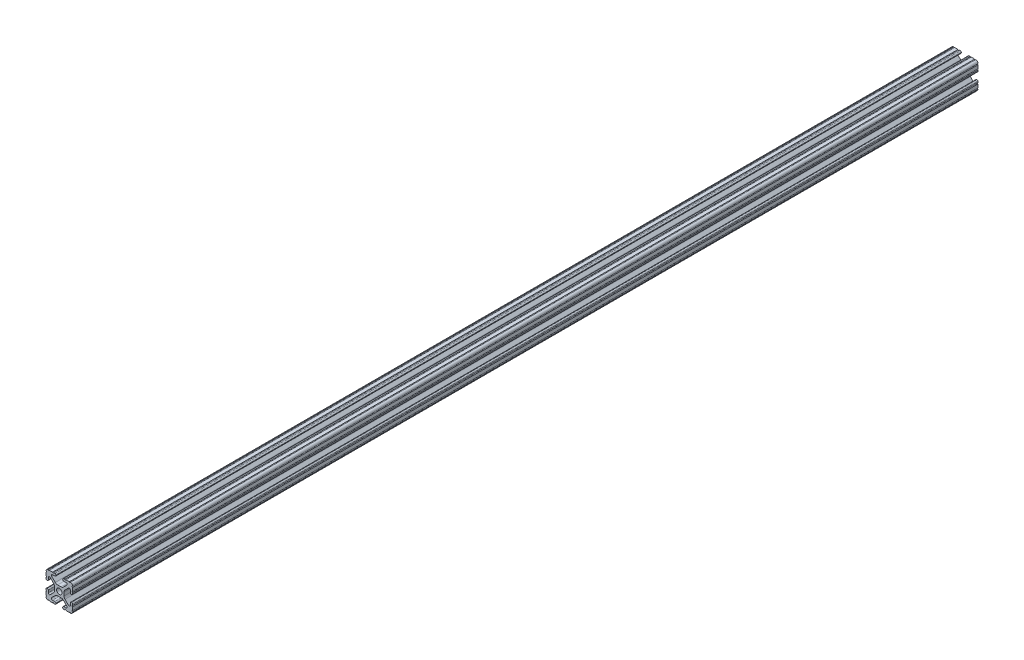
SolidWorks part; units mm, degrees
ref_plane "Front Plane" through (0, 0, 0) normal (0, 0, 1) x (1, 0, 0)
ref_plane "Top Plane" through (0, 0, 0) normal (0, 1, 0) x (1, 0, 0)
ref_plane "Right Plane" through (0, 0, 0) normal (1, 0, 0) x (0, 0, -1)
sketch "Sketch1" plane through (0, 0, 0) normal (0, 0, 1) x (1, 0, 0)
  line L88 (-7.1797, -8.6452) -> (-3.9523, -5.4237)
  line L89 (-1.7093, -4.4958) -> (1.7093, -4.4958)
  line L90 (3.9523, -5.4237) -> (7.1797, -8.6452)
  line L91 (6.4164, -10.4902) -> (4.2875, -10.4902)
  line L92 (3.2385, -11.5392) -> (3.2385, -11.651)
  line L93 (4.2875, -12.7) -> (5.3171, -12.7)
  line L94 (6.3331, -12.7) -> (9.5504, -12.7)
  line L95 (12.7, -9.5504) -> (12.7, -6.3331)
  line L96 (12.7, -5.3171) -> (12.7, -4.2875)
  line L97 (11.651, -3.2385) -> (11.5392, -3.2385)
  line L98 (10.4902, -4.2875) -> (10.4902, -6.4021)
  line L99 (8.7371, -7.1294) -> (5.441, -3.8408)
  line L100 (4.5085, -1.5932) -> (4.5085, 1.5932)
  line L101 (5.441, 3.8408) -> (8.7371, 7.1294)
  line L102 (10.4902, 6.4021) -> (10.4902, 4.2875)
  line L103 (11.5392, 3.2385) -> (11.651, 3.2385)
  line L104 (12.7, 4.2875) -> (12.7, 5.3171)
  line L105 (12.7, 6.3331) -> (12.7, 9.5504)
  line L106 (9.5504, 12.7) -> (6.3331, 12.7)
  line L107 (5.3171, 12.7) -> (4.2875, 12.7)
  line L108 (3.2385, 11.651) -> (3.2385, 11.5392)
  line L109 (4.2875, 10.4902) -> (6.4768, 10.4902)
  line L110 (7.207, 8.7244) -> (3.8983, 5.4232)
  line L111 (1.6558, 4.4958) -> (-1.6558, 4.4958)
  line L112 (-3.8983, 5.4232) -> (-7.207, 8.7244)
  line L113 (-6.4768, 10.4902) -> (-4.2875, 10.4902)
  line L114 (-3.2385, 11.5392) -> (-3.2385, 11.651)
  line L115 (-4.2875, 12.7) -> (-5.3171, 12.7)
  line L116 (-6.3331, 12.7) -> (-9.5504, 12.7)
  line L117 (-12.7, 9.5504) -> (-12.7, 6.3331)
  line L118 (-12.7, 5.3171) -> (-12.7, 4.2875)
  line L119 (-11.651, 3.2385) -> (-11.5392, 3.2385)
  line L120 (-10.4902, 4.2875) -> (-10.4902, 6.4021)
  line L121 (-8.7371, 7.1294) -> (-5.441, 3.8408)
  line L122 (-4.5085, 1.5932) -> (-4.5085, -1.5932)
  line L123 (-5.441, -3.8408) -> (-8.7371, -7.1294)
  line L124 (-10.4902, -6.4021) -> (-10.4902, -4.2875)
  line L125 (-11.5392, -3.2385) -> (-11.651, -3.2385)
  line L126 (-12.7, -4.2875) -> (-12.7, -5.3171)
  line L127 (-12.7, -6.3331) -> (-12.7, -9.5504)
  line L128 (-9.5504, -12.7) -> (-6.3331, -12.7)
  line L129 (-5.3171, -12.7) -> (-4.2875, -12.7)
  line L130 (-3.2385, -11.651) -> (-3.2385, -11.5392)
  line L131 (-4.2875, -10.4902) -> (-6.4164, -10.4902)
  circle A1 centre (0, 0) radius 2.6035
  arc A104 (-7.1797, -8.6452) -> (-6.4164, -10.4902) centre (-6.4164, -9.4098) ccw
  arc A105 (-1.7093, -4.4958) -> (-3.9523, -5.4237) centre (-1.7093, -7.6708) ccw
  arc A106 (3.9523, -5.4237) -> (1.7093, -4.4958) centre (1.7093, -7.6708) ccw
  arc A107 (6.4164, -10.4902) -> (7.1797, -8.6452) centre (6.4164, -9.4098) ccw
  arc A108 (4.2875, -10.4902) -> (3.2385, -11.5392) centre (4.2875, -11.5392) ccw
  arc A109 (3.2385, -11.651) -> (4.2875, -12.7) centre (4.2875, -11.651) ccw
  arc A110 (6.3331, -12.7) -> (5.3171, -12.7) centre (5.8251, -12.7) ccw
  arc A111 (10.5664, -12.6998) -> (9.5504, -12.7) centre (10.0584, -12.7) ccw
  arc A112 (10.5664, -12.6998) -> (12.6998, -10.5664) centre (10.5918, -10.5918) ccw
  arc A113 (12.7, -9.5504) -> (12.6998, -10.5664) centre (12.7, -10.0584) ccw
  arc A114 (12.7, -5.3171) -> (12.7, -6.3331) centre (12.7, -5.8251) ccw
  arc A115 (12.7, -4.2875) -> (11.651, -3.2385) centre (11.651, -4.2875) ccw
  arc A116 (11.5392, -3.2385) -> (10.4902, -4.2875) centre (11.5392, -4.2875) ccw
  arc A117 (8.7371, -7.1294) -> (10.4902, -6.4021) centre (9.4628, -6.4021) ccw
  arc A118 (4.5085, -1.5932) -> (5.441, -3.8408) centre (7.6835, -1.5932) ccw
  arc A119 (5.441, 3.8408) -> (4.5085, 1.5932) centre (7.6835, 1.5932) ccw
  arc A120 (10.4902, 6.4021) -> (8.7371, 7.1294) centre (9.4628, 6.4021) ccw
  arc A121 (10.4902, 4.2875) -> (11.5392, 3.2385) centre (11.5392, 4.2875) ccw
  arc A122 (11.651, 3.2385) -> (12.7, 4.2875) centre (11.651, 4.2875) ccw
  arc A123 (12.7, 6.3331) -> (12.7, 5.3171) centre (12.7, 5.8251) ccw
  arc A124 (12.6998, 10.5664) -> (12.7, 9.5504) centre (12.7, 10.0584) ccw
  arc A125 (12.6998, 10.5664) -> (10.5664, 12.6998) centre (10.5918, 10.5918) ccw
  arc A126 (9.5504, 12.7) -> (10.5664, 12.6998) centre (10.0584, 12.7) ccw
  arc A127 (5.3171, 12.7) -> (6.3331, 12.7) centre (5.8251, 12.7) ccw
  arc A128 (4.2875, 12.7) -> (3.2385, 11.651) centre (4.2875, 11.651) ccw
  arc A129 (3.2385, 11.5392) -> (4.2875, 10.4902) centre (4.2875, 11.5392) ccw
  arc A130 (7.207, 8.7244) -> (6.4768, 10.4902) centre (6.4768, 9.4563) ccw
  arc A131 (1.6558, 4.4958) -> (3.8983, 5.4232) centre (1.6558, 7.6708) ccw
  arc A132 (-3.8983, 5.4232) -> (-1.6558, 4.4958) centre (-1.6558, 7.6708) ccw
  arc A133 (-6.4768, 10.4902) -> (-7.207, 8.7244) centre (-6.4768, 9.4563) ccw
  arc A134 (-4.2875, 10.4902) -> (-3.2385, 11.5392) centre (-4.2875, 11.5392) ccw
  arc A135 (-3.2385, 11.651) -> (-4.2875, 12.7) centre (-4.2875, 11.651) ccw
  arc A136 (-6.3331, 12.7) -> (-5.3171, 12.7) centre (-5.8251, 12.7) ccw
  arc A137 (-10.5664, 12.6998) -> (-9.5504, 12.7) centre (-10.0584, 12.7) ccw
  arc A138 (-10.5664, 12.6998) -> (-12.6998, 10.5664) centre (-10.5918, 10.5918) ccw
  arc A139 (-12.7, 9.5504) -> (-12.6998, 10.5664) centre (-12.7, 10.0584) ccw
  arc A140 (-12.7, 5.3171) -> (-12.7, 6.3331) centre (-12.7, 5.8251) ccw
  arc A141 (-12.7, 4.2875) -> (-11.651, 3.2385) centre (-11.651, 4.2875) ccw
  arc A142 (-11.5392, 3.2385) -> (-10.4902, 4.2875) centre (-11.5392, 4.2875) ccw
  arc A143 (-8.7371, 7.1294) -> (-10.4902, 6.4021) centre (-9.4628, 6.4021) ccw
  arc A144 (-4.5085, 1.5932) -> (-5.441, 3.8408) centre (-7.6835, 1.5932) ccw
  arc A145 (-5.441, -3.8408) -> (-4.5085, -1.5932) centre (-7.6835, -1.5932) ccw
  arc A146 (-10.4902, -6.4021) -> (-8.7371, -7.1294) centre (-9.4628, -6.4021) ccw
  arc A147 (-10.4902, -4.2875) -> (-11.5392, -3.2385) centre (-11.5392, -4.2875) ccw
  arc A148 (-11.651, -3.2385) -> (-12.7, -4.2875) centre (-11.651, -4.2875) ccw
  arc A149 (-12.7, -6.3331) -> (-12.7, -5.3171) centre (-12.7, -5.8251) ccw
  arc A150 (-12.6998, -10.5664) -> (-12.7, -9.5504) centre (-12.7, -10.0584) ccw
  arc A151 (-12.6998, -10.5664) -> (-10.5664, -12.6998) centre (-10.5918, -10.5918) ccw
  arc A152 (-9.5504, -12.7) -> (-10.5664, -12.6998) centre (-10.0584, -12.7) ccw
  arc A153 (-5.3171, -12.7) -> (-6.3331, -12.7) centre (-5.8251, -12.7) ccw
  arc A154 (-4.2875, -12.7) -> (-3.2385, -11.651) centre (-4.2875, -11.651) ccw
  arc A155 (-3.2385, -11.5392) -> (-4.2875, -10.4902) centre (-4.2875, -11.5392) ccw
extrude "Boss-Extrude1" add sketch "Sketch1" along normal mid plane 863.6
